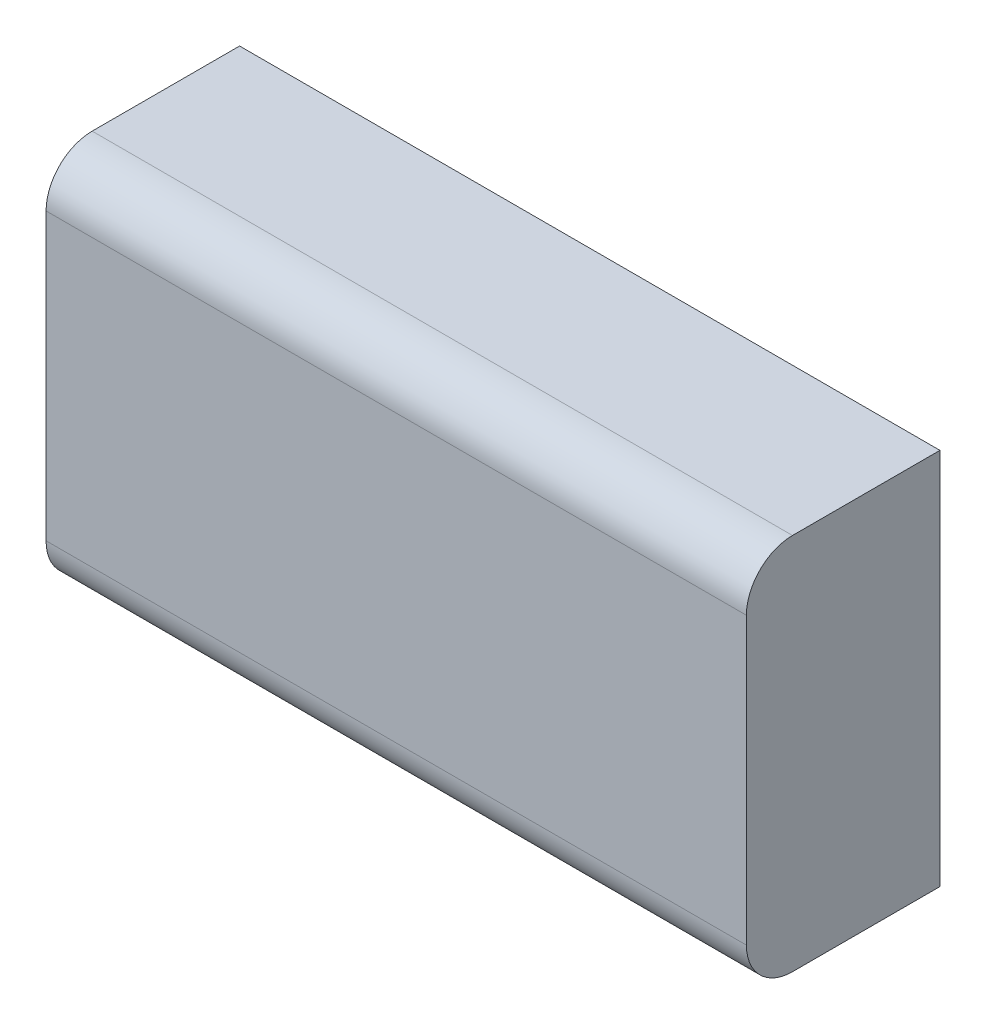
SolidWorks part; units mm, degrees
ref_plane "前视基准面" through (0, 0, 0) normal (0, 0, 1) x (1, 0, 0)
ref_plane "上视基准面" through (0, 0, 0) normal (0, 1, 0) x (1, 0, 0)
ref_plane "右视基准面" through (0, 0, 0) normal (1, 0, 0) x (0, 0, -1)
other "Configuration Table"
sketch "草图1" plane through (0, 0, 0) normal (0, 0, 1) x (1, 0, 0)
  line L1 (-38, 20.5) -> (38, 20.5)
  line L2 (-38, 20.5) -> (-38, -20.5)
  line L3 (-38, -20.5) -> (38, -20.5)
  line L4 (38, 20.5) -> (38, -20.5)
  line L5 (-38, 20.5) -> (38, -20.5) construction
  line L6 (-38, -20.5) -> (38, 20.5) construction
  point P0 (0, 0)
  dimension "D1" = 41
  dimension "D2" = 76
extrude "凸台-拉伸1" add sketch "草图1" along normal blind 21
fillet "圆角1" radius 5 2 edges at (0, -20.5, 21) (0, 20.5, 21)
